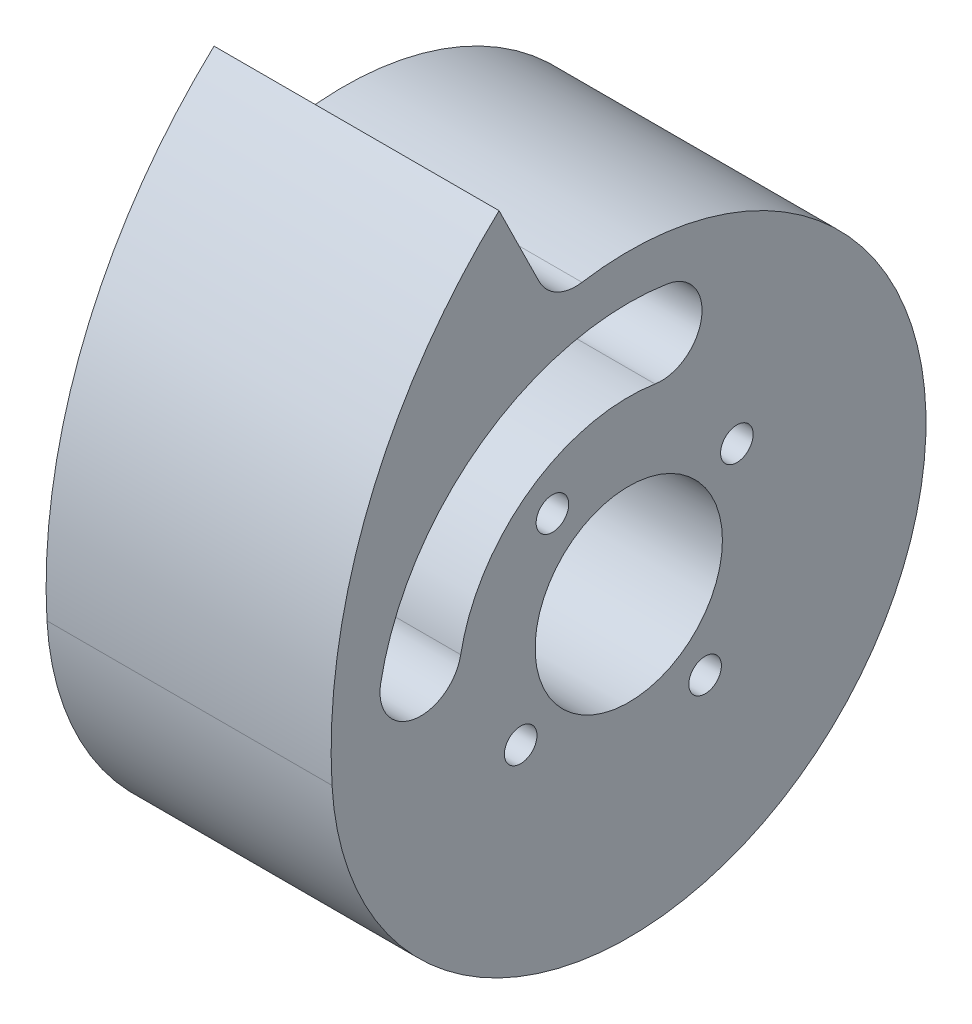
SolidWorks part; units mm, degrees
material "AISI 4340 Aço recozido"
ref_plane "Plano frontal" through (0, 0, 0) normal (0, 0, 1) x (1, 0, 0)
ref_plane "Plano superior" through (0, 0, 0) normal (0, 1, 0) x (1, 0, 0)
ref_plane "Plano direito" through (0, 0, 0) normal (1, 0, 0) x (0, 0, -1)
other "Center of Mass"
sketch "Esboço1" plane through (0, 0, 0) normal (1, 0, 0) x (0, 0, -1)
  line L0 (-15.9239, 48.7539) -> (-9.3015, 35.2949)
  circle A0 centre (0, 0) radius 36.5
  arc A1 (-15.9239, 48.7539) -> (-36.4394, -2.1024) centre (27.682, 1.5971) ccw
  arc A2 (-25.5485, 4.8242) -> (3.9957, 25.6911) centre (0, 0) cw construction
  circle A3 centre (0, 0) radius 11.5
  arc A4 (4.7641, 30.6317) -> (-30.4617, 5.7519) centre (0, 0) ccw
  arc A5 (3.2273, 20.7505) -> (-20.6354, 3.8964) centre (0, 0) ccw
  arc A6 (3.2273, 20.7505) -> (4.7641, 30.6317) centre (3.9957, 25.6911) ccw
  arc A7 (-30.4617, 5.7519) -> (-20.6354, 3.8964) centre (-25.5485, 4.8242) ccw
  circle A8 centre (0, 0) radius 51.2885
  point P10 (-14.9996, 21.237)
  point P13 (0, 0)
  point P16 (0, 0)
  dimension "D1" = 26
  dimension "D2" = 73
  dimension "D4" = 23
  dimension "D7" = 5
  dimension "D3" = 21
  dimension "D6" = 5
  dimension "D8" = 40
  dimension "D12" = 51.2885
  dimension "D5" = 15
extrude "Ressalto-extrusão1" add sketch "Esboço1" along normal mid plane 35
fillet "Fillet1" radius 5 1 edges at (0, 35.2949, 9.3015)
sketch "Esboço2" plane through (17.5, 0, 0) normal (1, 0, 0) x (0, 0, -1)
  line L0 (-12.1151, 17.153) -> (-9.3748, 13.2731) construction
  line L1 (-9.3748, 13.2731) -> (-6.6345, 9.3933) construction
  circle A0 centre (0, 0) radius 16.25 construction
  arc A1 (3.2273, 20.7505) -> (-20.6354, 3.8964) centre (0, 0) ccw construction
  circle A2 centre (0, 0) radius 11.5 construction
  circle A3 centre (-9.3748, 13.2731) radius 2
  circle A4 centre (13.2731, 9.3748) radius 2
  circle A5 centre (9.3748, -13.2731) radius 2
  circle A6 centre (-13.2731, -9.3748) radius 2
  point P19 (0, 0)
  dimension "D1" = 4
  dimension "D2" = 4
extrude "Corte-extrusão1" cut sketch "Esboço2" against normal blind 10
